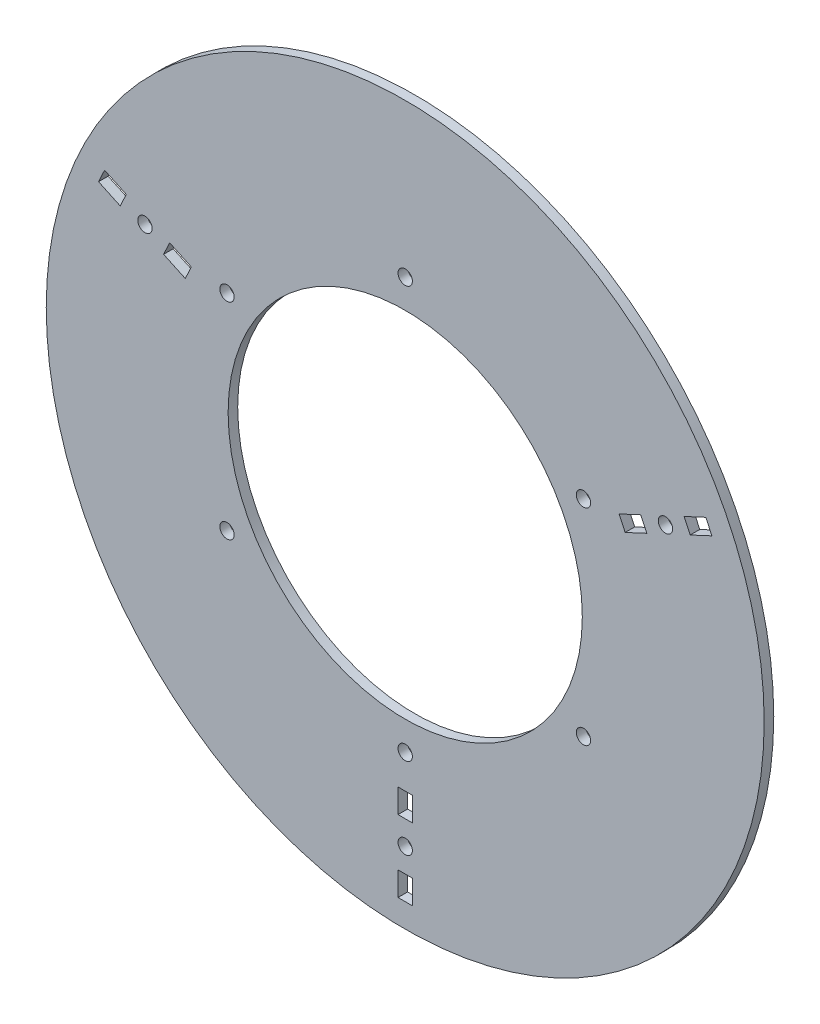
SolidWorks part; units mm, degrees
ref_plane "Front Plane" through (0, 0, 0) normal (0, 0, 1) x (1, 0, 0)
ref_plane "Top Plane" through (0, 0, 0) normal (0, 1, 0) x (1, 0, 0)
ref_plane "Right Plane" through (0, 0, 0) normal (1, 0, 0) x (0, 0, -1)
sketch "Sketch1" plane through (0, 0, 0) normal (0, 0, 1) x (1, 0, 0)
  line L0 (0, 0) -> (0, -75) construction
  line L1 (0, 0) -> (67.9731, 31.6964) construction
  line L2 (0, 0) -> (-67.9731, 31.6964) construction
  circle A0 centre (0, 0) radius 37
  circle A1 centre (0, 0) radius 75
  circle A2 centre (0, 0) radius 60 construction
  circle A3 centre (0, 0) radius 43 construction
  circle A4 centre (0, -43) radius 1.5
  circle A5 centre (-37.2391, -21.5) radius 1.5
  circle A6 centre (-37.2391, 21.5) radius 1.5
  circle A7 centre (0, 43) radius 1.5
  circle A8 centre (37.2391, 21.5) radius 1.5
  circle A9 centre (37.2391, -21.5) radius 1.5
  point P24 (0, 0)
  line B0 (0, -55) -> (0, -65) construction
  line B1 (1.5, -55) -> (1.5, -50)
  line B2 (1.5, -55) -> (-1.5, -55)
  line B3 (-1.5, -55) -> (-1.5, -50)
  line B4 (1.5, -50) -> (-1.5, -50)
  line B5 (1.5, -65) -> (1.5, -70)
  line B6 (1.5, -65) -> (-1.5, -65)
  line B7 (-1.5, -65) -> (-1.5, -70)
  line B8 (1.5, -70) -> (-1.5, -70)
  circle B9 centre (0, -60) radius 1.5
  line B10 (49.8469, 23.244) -> (58.91, 27.4702) construction
  line B11 (49.213, 24.6035) -> (44.6815, 22.4904)
  line B12 (49.213, 24.6035) -> (50.4809, 21.8845)
  line B13 (50.4809, 21.8845) -> (45.9493, 19.7715)
  line B14 (44.6815, 22.4904) -> (45.9493, 19.7715)
  line B15 (58.2761, 28.8296) -> (62.8076, 30.9427)
  line B16 (58.2761, 28.8296) -> (59.5439, 26.1107)
  line B17 (59.5439, 26.1107) -> (64.0755, 28.2238)
  line B18 (62.8076, 30.9427) -> (64.0755, 28.2238)
  circle B19 centre (54.3785, 25.3571) radius 1.5
  line B20 (-58.91, 27.4702) -> (-49.8469, 23.244) construction
  line B21 (-58.2761, 28.8296) -> (-62.8076, 30.9427)
  line B22 (-58.2761, 28.8296) -> (-59.5439, 26.1107)
  line B23 (-59.5439, 26.1107) -> (-64.0755, 28.2238)
  line B24 (-62.8076, 30.9427) -> (-64.0755, 28.2238)
  line B25 (-49.213, 24.6035) -> (-44.6815, 22.4904)
  line B26 (-49.213, 24.6035) -> (-50.4809, 21.8845)
  line B27 (-50.4809, 21.8845) -> (-45.9493, 19.7715)
  line B28 (-44.6815, 22.4904) -> (-45.9493, 19.7715)
  circle B29 centre (-54.3785, 25.3571) radius 1.5
  dimension "D1" = 74
  dimension "D2" = 150
  dimension "D4" = 120
  dimension "D5" = 6
  dimension "D6" = 3
  dimension "D3" = 115
  dimension "D7" = 6
sketch_block_instance "Trou M3 plots 3mm-1"
sketch_block "Trou M3 plots 3mm" parameters "D2"=3, "D1"=3, "D3"=5, "D4"=10
sketch_block_instance "Trou M3 plots 3mm-2"
sketch_block_instance "Trou M3 plots 3mm-3"
extrude "Boss-Extrude1" add sketch "Sketch1" along normal blind 2
